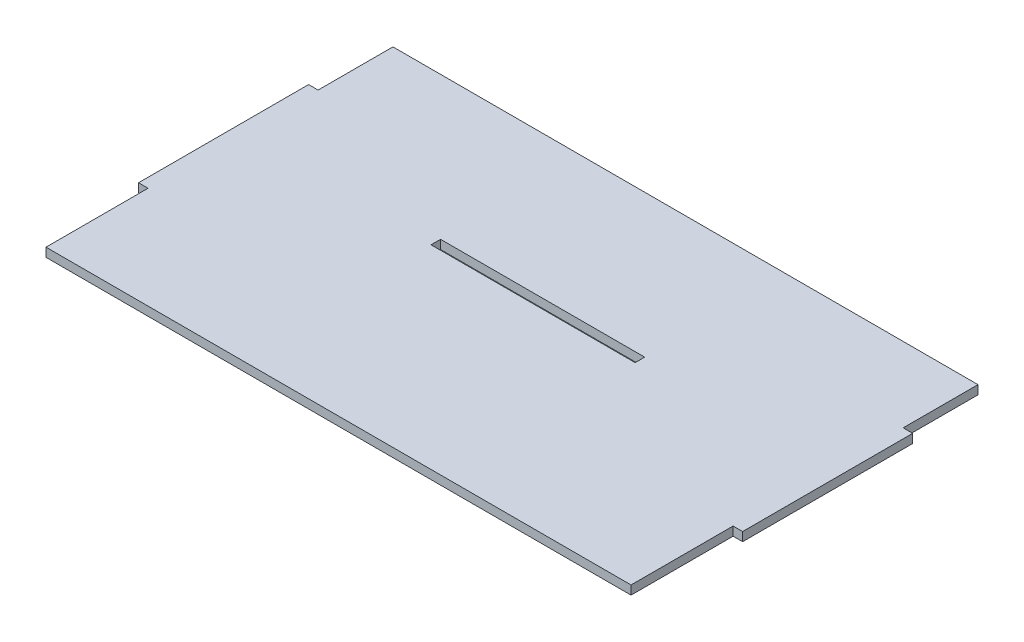
SolidWorks part; units mm, degrees
ref_plane "Front Plane" through (0, 0, 0) normal (0, 0, 1) x (1, 0, 0)
ref_plane "Top Plane" through (0, 0, 0) normal (0, 1, 0) x (1, 0, 0)
ref_plane "Right Plane" through (0, 0, 0) normal (1, 0, 0) x (0, 0, -1)
sketch "Sketch1" plane through (0, 0, 0) normal (0, 1, 0) x (1, 0, 0)
  line L1 (-43, 25) -> (43, 25)
  line L2 (-43, 25) -> (-43, -25)
  line L3 (-43, -25) -> (43, -25)
  line L4 (43, 25) -> (43, -25)
  line L5 (-43, 25) -> (43, -25) construction
  line L6 (-43, -25) -> (43, 25) construction
  point P0 (0, 0)
  dimension "D1" = 86
  dimension "D2" = 50
extrude "Boss-Extrude1" add sketch "Sketch1" along normal blind 1.3
sketch "Sketch2" plane through (0, 1.3, 0) normal (0, 1, 0) x (1, 0, 0)
  line L0 (-43, 25) -> (-43, -25) construction
  line L1 (-43, 15) -> (-44.4, 15)
  line L2 (-43, 15) -> (-43, -10)
  line L3 (-43, -10) -> (-44.4, -10)
  line L4 (-44.4, 15) -> (-44.4, -10)
  line L5 (43, -25) -> (43, 25) construction
  line L6 (43, 15) -> (44.4, 15)
  line L7 (43, 15) -> (43, -10)
  line L8 (43, -10) -> (44.4, -10)
  line L9 (44.4, 15) -> (44.4, -10)
  line L10 (43, 25) -> (-43, 25) construction
  dimension "D1" = 1.4
  dimension "D2" = 1.4
  dimension "D3" = 25
  dimension "D4" = 25
  dimension "D5" = 10
  dimension "D6" = 10
extrude "Boss-Extrude2" add sketch "Sketch2" against normal blind 1.3
sketch "Sketch3" plane through (0, 1.3, 0) normal (0, 1, 0) x (1, 0, 0)
  line L0 (-43, 15) -> (43, 15) construction
  line L1 (0, -0.715) -> (0, 0.715) construction
  line L2 (-15, 5) -> (15, 5)
  line L3 (-15, 5) -> (-15, 3.6)
  line L4 (-15, 3.6) -> (15, 3.6)
  line L5 (15, 5) -> (15, 3.6)
  line L6 (-15, 5) -> (15, 3.6) construction
  line L7 (-15, 3.6) -> (15, 5) construction
  point P4 (0, 4.3)
  dimension "D1" = 1.4
  dimension "D2" = 30
  dimension "D3" = 10
extrude "Cut-Extrude1" cut sketch "Sketch3" against normal through all
sketch "Sketch4" plane through (0, 0, 0) normal (0, 1, 0) x (1, 0, 0)
  line L1 (-43, 25) -> (43, 25)
  line L2 (-43, 25) -> (-43, 26)
  line L3 (-43, 26) -> (43, 26)
  line L4 (43, 25) -> (43, 26)
  dimension "D1" = 86
  dimension "D2" = 1
extrude "Boss-Extrude3" add sketch "Sketch4" along normal blind 1.3
